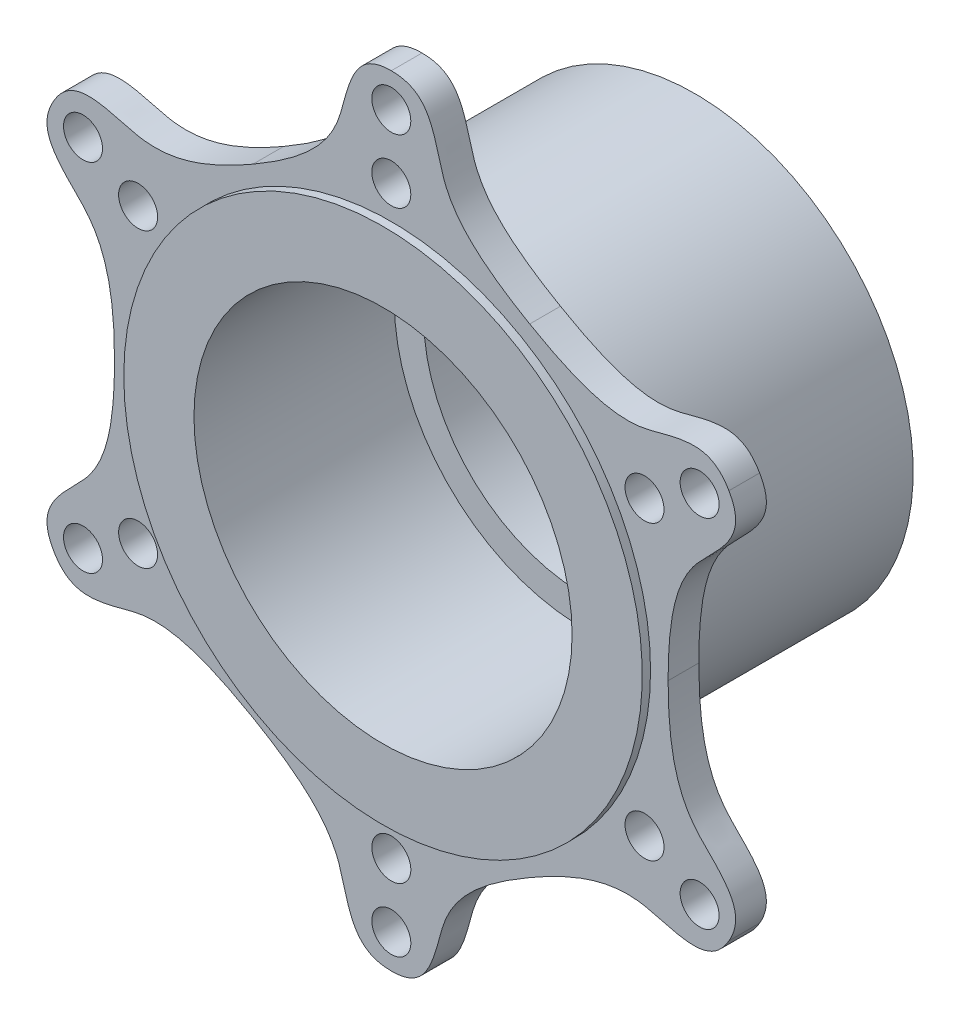
SolidWorks part; units mm, degrees
material "6061-T6 (SS)"
ref_plane "Front Plane" through (0, 0, 0) normal (0, 0, 1) x (1, 0, 0)
ref_plane "Top Plane" through (0, 0, 0) normal (0, 1, 0) x (1, 0, 0)
ref_plane "Right Plane" through (0, 0, 0) normal (1, 0, 0) x (0, 0, -1)
ref_axis "Axis1" through (0, 0, -58.1544) along (0, 0, 1)
sketch "Sketch1" plane through (0, 0, 0) normal (1, 0, 0) x (0, 0, -1)
  line L0 (0, 0) -> (-50000, 0) construction
  line L1 (0, 63.5) -> (-5.0038, 63.5)
  line L2 (-5.0038, 63.5) -> (-5.0038, 30.7975)
  line L3 (-5.0038, 30.7975) -> (26.2712, 30.7975)
  line L4 (26.2712, 30.7975) -> (26.2712, 26)
  line L5 (26.2712, 26) -> (41.2712, 26)
  line L6 (0, 63.5) -> (0, 35.56)
  line L7 (41.2712, 26) -> (41.2712, 22.825)
  line L8 (41.2712, 22.825) -> (44.4462, 22.825)
  line L9 (44.4462, 22.825) -> (44.4462, 35.56)
  line L12 (44.4462, 35.56) -> (0, 35.56)
  dimension "D1" = 5.0038
  dimension "D2" = 52
  dimension "D3" = 4.7625
  dimension "D4" = 3.175
  dimension "D5" = 49.45
  dimension "D6" = 15
  dimension "D7" = 3.175
  dimension "D9" = 63.5
  dimension "D10" = 35.56
revolve "Revolve1" add sketch "Sketch1" angle 360 about L0
sketch "Sketch3" plane through (0, 0, 5.0038) normal (0, 0, 1) x (1, 0, 0)
  line L0 (0, 57.9882) -> (0, 0) construction
  circle A0 centre (0, 57.9882) radius 3.175
  circle A1 centre (0, 47.625) radius 3.175
  dimension "D1" = 6.35
  dimension "D4" = 6.35
  dimension "D2" = 57.9882
  dimension "D3" = 47.625
extrude "Extrude2" cut sketch "Sketch3" against normal up to next
pattern_circular "CirPattern2" count 6 over 360 about axis through (0, 0, 0) along (0, 0, 1) of "Extrude2"
sketch "Sketch4" plane through (0, 0, -44.4462) normal (0, 0, -1) x (-1, 0, 0)
  line L0 (0, 0) -> (0, 55) construction
  circle A0 centre (0, 55) radius 5.1
  circle A1 centre (0, 41.275) radius 3.9688
  dimension "D1" = 10.2
  dimension "D3" = 7.9375
  dimension "D2" = 55
  dimension "D4" = 41.275
extrude "Extrude3" [suppressed] cut sketch "Sketch4" against normal up to next
pattern_circular "CirPattern3" [suppressed] count 5 over 360 about axis through (0, 0, -58.1544) along (0, 0, 1)
sketch "Sketch9" plane through (0, 0, 0) normal (0, 0, 1) x (1, 0, 0)
  line L0 (0, 0) -> (51.1012, 88.5099) construction
  line L1 (0, 0) -> (0, 86.0554) construction
  line L2 (0, 0) -> (78.6704, 45.4204) construction
  line L3 (25.6183, 39.7619) -> (21.6257, 42.0671) construction
  arc A1 (54.9926, 31.75) -> (0, 63.5) centre (0, 0) ccw
  spline S0 degree 3 poles (0, 63.5) (6.0754, 63.5) (9.0354, 53.5896) (12.7049, 47.2175) (23.622, 40.9145) knots 0 0 0 0 0.515622 1 1 1 1
  spline S1 degree 3 poles (54.9926, 31.75) (51.9549, 37.0115) (41.8923, 34.6197) (34.5391, 34.6115) (23.622, 40.9145) knots 0 0 0 0 0.515622 1 1 1 1
  point P6 (23.495, 40.6945)
  dimension "D1" = 30
  dimension "D2" = 0.254
sketch "Sketch6" plane through (0, 0, 0) normal (0, 0, 1) x (1, 0, 0)
  line L0 (0, 0) -> (48.8892, 84.6786) construction
  line L1 (0, 0) -> (0, 82.2242) construction
  line L2 (0, 0) -> (76.4584, 41.5891) construction
  line L3 (24.5388, 37.8922) -> (20.5462, 40.1973) construction
  line L4 (0, 0) -> (51.1012, 88.5099) construction
  arc A1 (54.9926, 31.75) -> (0, 63.5) centre (0, 0) ccw
  circle A4 centre (0, 0) radius 35.56 construction
  spline S0 degree 3 poles (0, 63.5) (5.057, 63.5) (6.7112, 59.4602) (9.4881, 48.4036) (14.6671, 43.5916) (22.5425, 39.0448) knots 0 0 0 0 0.460561 0.560561 1 1 1 1
  spline S1 degree 3 poles (54.9926, 31.75) (52.4641, 36.1295) (48.1384, 35.5422) (37.1747, 32.4187) (30.4179, 34.4979) (22.5425, 39.0448) knots 0 0 0 0 0.460561 0.560561 1 1 1 1
  point P6 (17.78, 30.7959)
  dimension "D1" = 30
  dimension "D2" = 9.525
extrude "Cut-Extrude1" cut sketch "Sketch6" along normal through all
pattern_circular "CirPattern4" count 6 over 360 about axis through (0, 0, -58.1544) along (0, 0, 1) of "Cut-Extrude1"
sketch "Sketch7" [suppressed] plane through (0, 0, -39.6875) normal (0, 0, -1) x (-1, 0, 0)
  line L0 (0, 0) -> (47.3181, 65.1277) construction
  line L1 (0, 0) -> (72.585, 23.5843) construction
  line L2 (0, 0) -> (0, 68.4808) construction
  line L3 (0, 55) -> (47.3181, 65.1277) construction
  line L4 (47.3181, 65.1277) -> (52.3081, 16.9959) construction
  line L5 (25.6318, 24.5471) -> (15.425, 31.9627) construction
  circle A0 centre (52.3081, 16.9959) radius 5.1 construction
  circle A1 centre (0, 0) radius 63.5
  arc A2 (60.3921, 19.6226) -> (0, 63.5) centre (0, 0) ccw
  circle A3 centre (52.3081, 16.9959) radius 5.1 construction
  circle A5 centre (0, 0) radius 34.925 construction
  circle A6 centre (0, 0) radius 34.925 construction
  circle A7 centre (0, 0) radius 63.5 construction
  spline S0 degree 3 poles (0, 63.5) (14.7696, 63.5) (6.2437, 38.6334) (20.5284, 28.2549) knots 0 0 0 0 1 1 1 1
  spline S1 degree 3 poles (60.3921, 19.6226) (55.828, 33.6693) (34.8131, 17.8765) (20.5284, 28.2549) knots 0 0 0 0 1 1 1 1
  dimension "D2" = 34.925
  dimension "D1" = 0
extrude "Cut-Extrude2" [suppressed] cut sketch "Sketch7" against normal up to next
pattern_circular "CirPattern5" [suppressed] count 5 over 360 about axis through (0, 0, -58.1544) along (0, 0, 1)
sketch "Sketch10" plane through (0, 0, 5.0038) normal (0, 0, 1) x (1, 0, 0)
  circle A0 centre (0, 0) radius 30.7975 construction
  circle A1 centre (0, 0) radius 30.7975
  circle A2 centre (0, 0) radius 42.2275
  dimension "D1" = 84.455
extrude "Boss-Extrude1" add sketch "Sketch10" along normal offset from surface (1.35 mm away) 50.8 up to face at (-35.56, 0, -44.4462)
sketch "Sketch11" plane through (0, 0, -44.4462) normal (0, 0, -1) x (-1, 0, 0)
  circle A0 centre (0, 30.9562) radius 2.3813
  circle A1 centre (0, 0) radius 30.9562 construction
  dimension "D1" = 4.7625
  dimension "D2" = 61.9125
extrude "Cut-Extrude4" cut sketch "Sketch11" against normal blind 12.7
pattern_circular "CirPattern6" count 6 over 360 about axis through (0, 0, 0) along (0, 0, 1) of "Cut-Extrude4"
fillet "Fillet1" radius 0.7937 1 edges at (-35.56, 0, 0)
